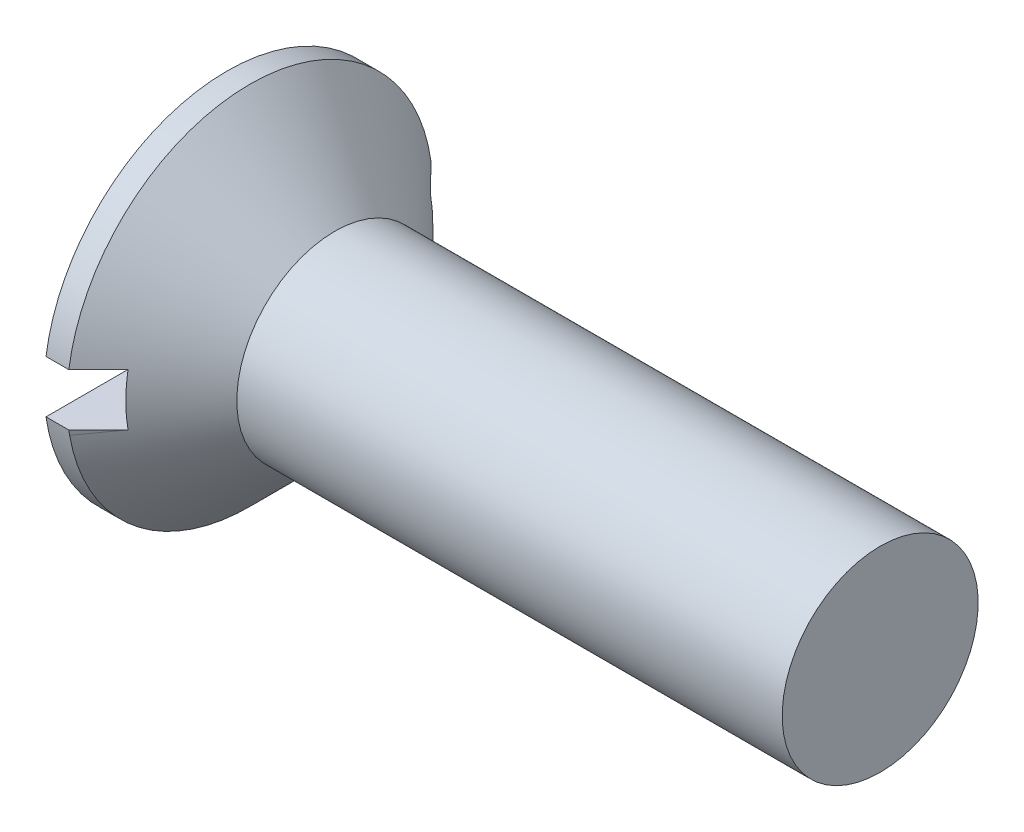
SolidWorks part; units mm, degrees
material "Plain Carbon Steel"
ref_plane "Front Plane" through (0, 0, 0) normal (0, 0, 1) x (1, 0, 0)
ref_plane "Top Plane" through (0, 0, 0) normal (0, 1, 0) x (1, 0, 0)
ref_plane "Right Plane" through (0, 0, 0) normal (1, 0, 0) x (0, 0, -1)
sketch "Sketch1" plane through (0, 0, 0) normal (0, 0, 1) x (1, 0, 0)
  line L0 (0, 0) -> (0, 2.8)
  line L1 (0, 2.8) -> (0.35, 2.8)
  line L2 (0.35, 2.8) -> (1.65, 1.5)
  line L3 (1.65, 1.5) -> (10, 1.5)
  line L4 (10, 1.5) -> (10, 0)
  line L5 (10, 0) -> (0, 0) construction
  line L6 (0, 0) -> (10, 0)
  dimension "D1" = 45
  dimension "D2" = 3
  dimension "D3" = 5.6
  dimension "D4" = 1.65
  dimension "D5" = 10
revolve "Revolve1" add sketch "Sketch1" angle 360 about L5
sketch "Sketch2" plane through (0, 0, 0) normal (-1, 0, 0) x (0, 0, 1)
  line L0 (2.8, 0) -> (-2.8, 0) construction
  line L1 (-2.8, 0.4) -> (2.8, 0.4)
  line L2 (-2.8, 0.4) -> (-2.8, -0.4)
  line L3 (-2.8, -0.4) -> (2.8, -0.4)
  line L4 (2.8, 0.4) -> (2.8, -0.4)
  circle A0 centre (0, 0) radius 2.8 construction
  dimension "D1" = 0.8
extrude "Cut-Extrude1" cut sketch "Sketch2" against normal blind 0.8
